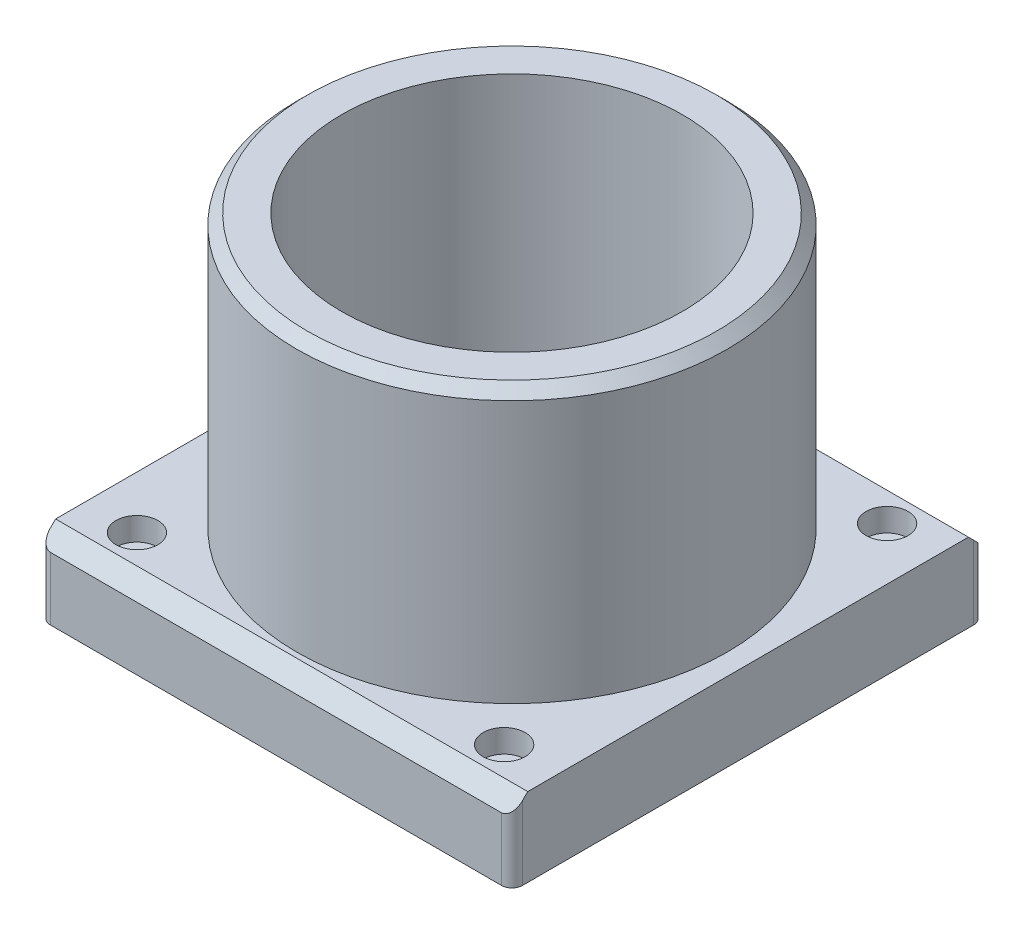
SolidWorks part; units mm, degrees
material "3.1305 (EN-AW 2117)"
ref_plane "Plan de face" through (0, 0, 0) normal (0, 0, 1) x (1, 0, 0)
ref_plane "Plan de dessus" through (0, 0, 0) normal (0, 1, 0) x (1, 0, 0)
ref_plane "Plan de droite" through (0, 0, 0) normal (1, 0, 0) x (0, 0, -1)
sketch "Esquisse1" plane through (0, 0, 0) normal (0, 1, 0) x (1, 0, 0)
  line L0 (0, 0) -> (0, 45) construction
  line L1 (-45, 45) -> (45, 45)
  line L2 (-45, 45) -> (-45, -45)
  line L3 (-45, -45) -> (45, -45)
  line L4 (45, 45) -> (45, -45)
  line L6 (45, 0) -> (0, 0) construction
  dimension "D1" = 90
extrude "Boss.-Extru.1" add sketch "Esquisse1" along normal blind 15
sketch "Esquisse2" plane through (0, 15, 0) normal (0, 1, 0) x (1, 0, 0)
  circle A0 centre (0, 0) radius 41
  dimension "D1" = 82
extrude "Boss.-Extru.2" add sketch "Esquisse2" along normal blind 52
chamfer "Chanfrein1" distance 3 angle 45 2 edges at (0, 15, -45) (0, 15, 45)
fillet "Congé1" radius 2 4 edges at (-45, 6, -45) (45, 6, -45) (45, 6, 45) (-45, 6, 45)
chamfer "Chanfrein2" distance 2 angle 45 1 edges at (0, 67, 41)
sketch "Esquisse3" plane through (0, 15, 0) normal (0, 1, 0) x (1, 0, 0)
  line L0 (0, 0) -> (0, -36.5) construction
  line L1 (35, -36.5) -> (-35, -36.5) construction
  line L2 (35, -36.5) -> (35, 36.5) construction
  line L3 (35, 36.5) -> (-35, 36.5) construction
  line L4 (-35, -36.5) -> (-35, 36.5) construction
  line L6 (-35, 0) -> (0, 0) construction
  dimension "D1" = 70
  dimension "D2" = 73
hole_wizard "Chambrage pour vis à tête hexagonale M41" positions "Esquisse5" profile "Esquisse4" counterbore size "M4" standard "Din" end condition through all
sketch "Esquisse5" plane through (0, 15, 0) normal (0, 1, 0) x (1, 0, 0)
  point P0 (-35, 36.5)
  point P3 (35, 36.5)
  point P6 (-35, -36.5)
  point P9 (35, -36.5)
sketch "Esquisse4" plane through (-35, 15, -36.5) normal (1, 0, 0) x (0, 0, 1)
  line L0 (0, 0) -> (0, 15)
  line L1 (0, 15) -> (2.25, 15)
  line L3 (2.25, 15) -> (2.25, 4.4)
  line L4 (2.25, 4.4) -> (4, 4.4)
  line L5 (4, 4.4) -> (4, 0)
  line L7 (4, 0) -> (0, 0)
  line L11 (0, -6.35) -> (0, 107.95) construction
  dimension "Diamètre du perçage jusqu'au prochain" = 4.5
  dimension "Profondeur du perçage jusqu'au prochain" = 15
  dimension "Diamètre du chambrage" = 8
  dimension "Profondeur du chambrage" = 4.4
sketch "Esquisse6" plane through (0, 67, 0) normal (0, 1, 0) x (1, 0, 0)
  circle A0 centre (0, 0) radius 32.5
  dimension "D1" = 65
extrude "Enlèv. mat.-Extru.1" cut sketch "Esquisse6" against normal through all
